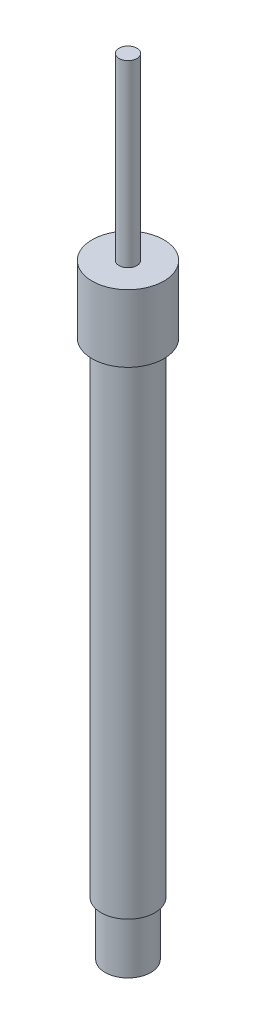
SolidWorks part; units mm, degrees
ref_plane "Front Plane" through (0, 0, 0) normal (0, 0, 1) x (1, 0, 0)
ref_plane "Top Plane" through (0, 0, 0) normal (0, 1, 0) x (1, 0, 0)
ref_plane "Right Plane" through (0, 0, 0) normal (1, 0, 0) x (0, 0, -1)
other "Configuration Table"
sketch "Sketch1" plane through (0, 0, 0) normal (0, 1, 0) x (1, 0, 0)
  circle A0 centre (0, 0) radius 5.1
extrude "Glass_Tip" add sketch "Sketch1" along normal blind 12
sketch "Sketch2" plane through (0, 0, 0) normal (0, 1, 0) x (1, 0, 0)
  circle A0 centre (0, 0) radius 6
  dimension "D1" = 12
extrude "Body" add sketch "Sketch2" along normal blind 108 from offset 12
sketch "Sketch3" plane through (0, 0, 0) normal (0, 1, 0) x (1, 0, 0)
  circle A0 centre (0, 0) radius 8
extrude "Cap" add sketch "Sketch3" along normal blind 15 from offset 120
sketch "Sketch4" plane through (0, 0, 0) normal (0, 1, 0) x (1, 0, 0)
  circle A0 centre (0, 0) radius 2
extrude "Cable" add sketch "Sketch4" along normal blind 40 from offset 135
equation "\"orp_D\"= 12.0   'ASSUMPTION: ORP electrode body OD (PDF fallback)"
equation "\"orp_L\"= 120.0   'ASSUMPTION: ORP electrode length (PDF fallback)"
equation "\"cable_D\"= 4.0   'ASSUMPTION: Probe cable OD (designer choice)"
equation "\"D1@Sketch2\" = \"orp_D\""
